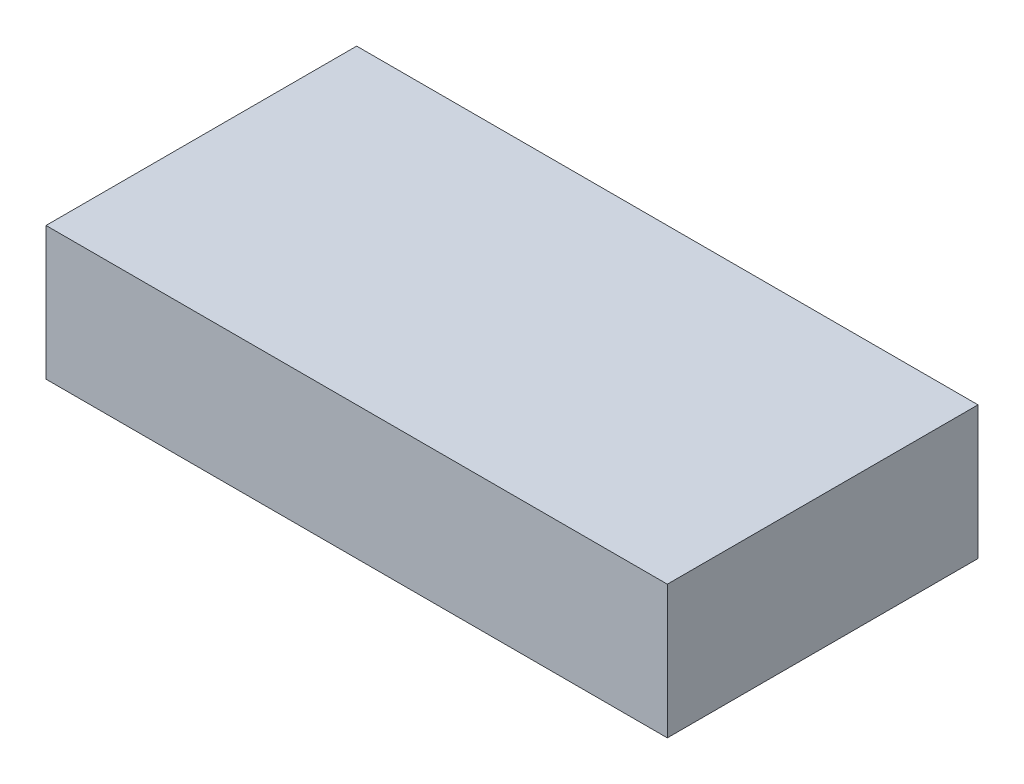
SolidWorks part; units mm, degrees
ref_plane "Front Plane" through (0, 0, 0) normal (0, 0, 1) x (1, 0, 0)
ref_plane "Top Plane" through (0, 0, 0) normal (0, 1, 0) x (1, 0, 0)
ref_plane "Right Plane" through (0, 0, 0) normal (1, 0, 0) x (0, 0, -1)
sketch "Sketch2" plane through (0, 0, 0) normal (0, 1, 0) x (1, 0, 0)
  line L0 (44.45, 22.225) -> (44.45, -22.225)
  line L1 (44.45, 22.225) -> (-44.45, 22.225)
  line L2 (44.45, -22.225) -> (-44.45, -22.225)
  line L3 (-44.45, 22.225) -> (-44.45, -22.225)
  line L4 (-44.45, 22.225) -> (44.45, -22.225) construction
  dimension "D1" = 44.45
  dimension "D2" = 88.9
extrude "Boss-Extrude1" add sketch "Sketch2" along normal blind 19.05
